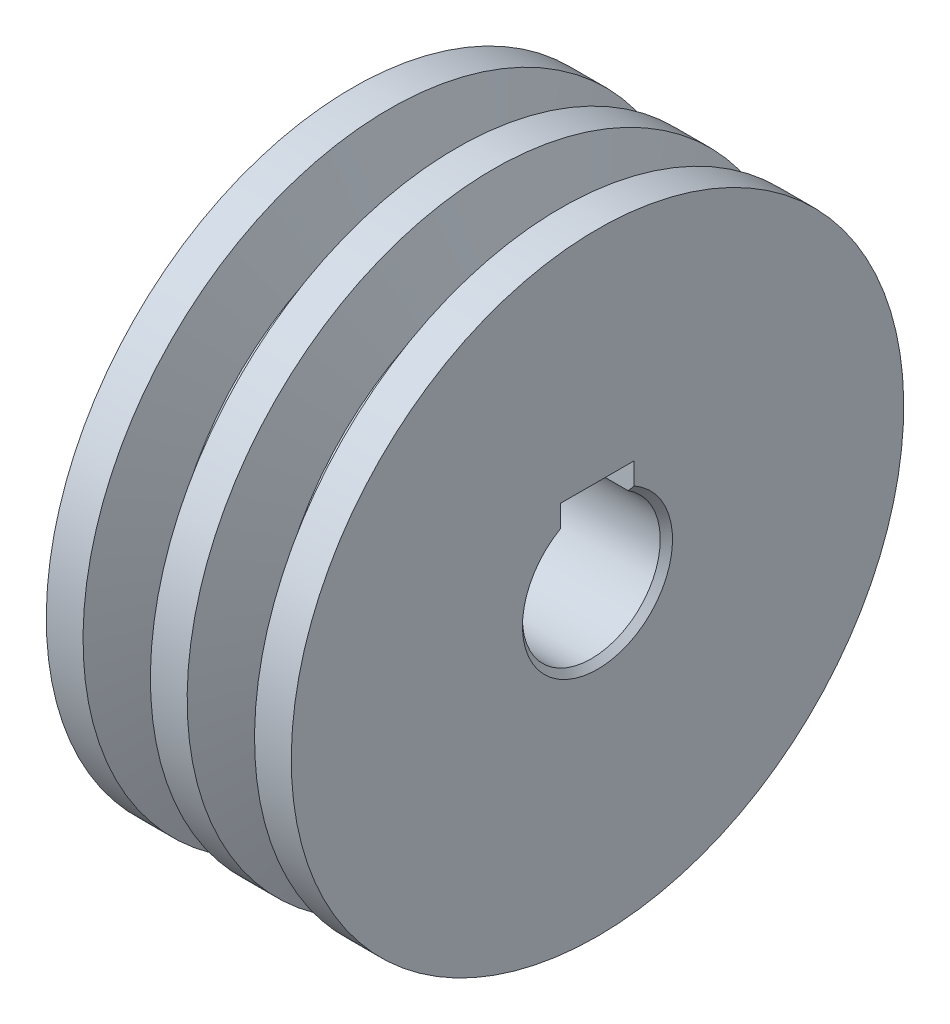
SolidWorks part; units mm, degrees
ref_plane "Front Plane" through (0, 0, 0) normal (0, 0, 1) x (1, 0, 0)
ref_plane "Top Plane" through (0, 0, 0) normal (0, 1, 0) x (1, 0, 0)
ref_plane "Right Plane" through (0, 0, 0) normal (1, 0, 0) x (0, 0, -1)
sketch "Sketch1" plane through (0, 0, 0) normal (0, 0, 1) x (1, 0, 0)
  line L0 (0, 50) -> (0, 0) construction
  line L1 (3, 50) -> (-3, 50)
  line L2 (-3, 50) -> (-6.6397, 40)
  line L3 (-6.6397, 40) -> (-10.3603, 40)
  line L4 (-10.3603, 40) -> (-14, 50)
  line L5 (-14, 50) -> (-20, 50)
  line L6 (-20, 50) -> (-20, 0)
  line L7 (-20, 0) -> (20, 0)
  line L8 (20, 50) -> (20, 0)
  line L9 (3, 50) -> (6.6397, 40)
  line L10 (6.6397, 40) -> (10.3603, 40)
  line L11 (10.3603, 40) -> (14, 50)
  line L12 (14, 50) -> (20, 50)
  dimension "D1" = 50
  dimension "D2" = 20
  dimension "D3" = 6
  dimension "D4" = 40
  dimension "D5" = 3
  dimension "D6" = 110
  dimension "D7" = 110
  dimension "D8" = 50
revolve "Revolve12" add sketch "Sketch1" angle 360 about L7
sketch "Sketch2" plane through (-20, 0, 0) normal (-1, 0, 0) x (0, 0, 1)
  circle A0 centre (0, 0) radius 25
  dimension "D1" = 50
extrude "Boss-Extrude1" add sketch "Sketch2" along normal blind 10
sketch "Sketch4" plane through (-30, 0, 0) normal (-1, 0, 0) x (0, 0, 1)
  line L1 (-6, 8.25) -> (6, 8.25)
  line L2 (-6, 8.25) -> (-6, 14.25)
  line L3 (-6, 14.25) -> (6, 14.25)
  line L4 (6, 8.25) -> (6, 14.25)
  line L5 (-6, 8.25) -> (6, 14.25) construction
  line L6 (-6, 14.25) -> (6, 8.25) construction
  circle A0 centre (0, 0) radius 11.25
  point P3 (0, 11.25)
  dimension "D1" = 22.5
  dimension "D2" = 12
  dimension "D3" = 6
extrude "Cut-Extrude1" cut sketch "Sketch4" against normal through all contours L2 A0 L4 L1
fillet "Fillet1" radius 0.2 1 edges at (-20, 25, 0)
chamfer "Chamfer1" distance 1 angle 45 1 edges at (20, -11.25, 0)
chamfer "Chamfer2" distance 1 angle 45 1 edges at (-30, -11.25, 0)
